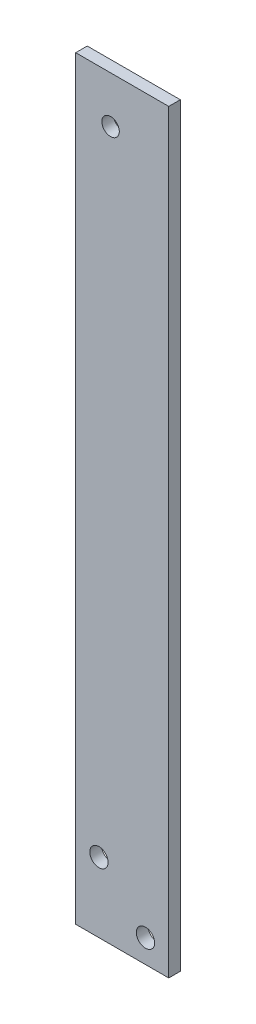
SolidWorks part; units mm, degrees
ref_plane "Alzado" through (0, 0, 0) normal (0, 0, 1) x (1, 0, 0)
ref_plane "Planta" through (0, 0, 0) normal (0, 1, 0) x (1, 0, 0)
ref_plane "Vista lateral" through (0, 0, 0) normal (1, 0, 0) x (0, 0, -1)
sketch "Croquis2" plane through (0, 0, 0) normal (0, 0, 1) x (1, 0, 0)
  line L0 (0, 0) -> (50.8, 0)
  line L1 (50.8, 0) -> (50.8, -361.2957)
  line L2 (50.8, -361.2957) -> (50.8, -412.0957)
  line L3 (50.8, -412.0957) -> (0, -412.0957)
  line L4 (0, -412.0957) -> (0, 0)
  dimension "D1" = 50.8
  dimension "D2" = 412.0957
extrude "Saliente-Extruir1" add sketch "Croquis2" along normal blind 6.31
sketch "Croquis3" plane through (0, 0, 6.31) normal (0, 0, 1) x (1, 0, 0)
  line L0 (19.04, -30.1625) -> (19.04, -25.4) construction
  line L1 (19.04, -25.4) -> (23.8025, -25.4) construction
  circle A0 centre (19.04, -25.4) radius 4.7625 construction
  circle A1 centre (19.04, -25.4) radius 4.7625
  dimension "D1" = 9.525
extrude "Cortar-Extruir1" cut sketch "Croquis3" against normal blind 9.525
sketch "Croquis4" plane through (0, 0, 6.31) normal (0, 0, 1) x (1, 0, 0)
  line L0 (12.7, -378.9957) -> (12.7, -373.9957) construction
  line L1 (12.7, -373.9957) -> (38.1, -399.3957) construction
  circle A0 centre (12.7, -373.9957) radius 5 construction
  circle A1 centre (12.7, -373.9957) radius 5
  circle A2 centre (38.1, -399.3957) radius 5
extrude "Cortar-Extruir2" cut sketch "Croquis4" against normal blind 9.525
